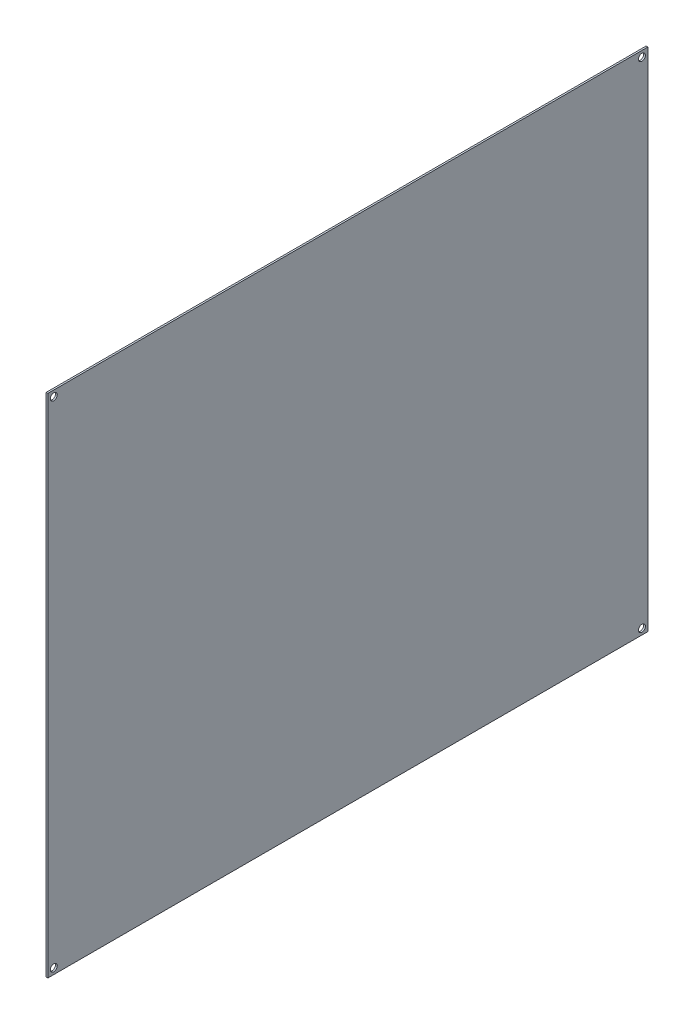
SolidWorks part; units mm, degrees
ref_plane "Front Plane" through (0, 0, 0) normal (0, 0, 1) x (1, 0, 0)
ref_plane "Top Plane" through (0, 0, 0) normal (0, 1, 0) x (1, 0, 0)
ref_plane "Right Plane" through (0, 0, 0) normal (1, 0, 0) x (0, 0, -1)
sketch "Sketch1" plane through (-873.1278, 0, 0) normal (-1, 0, 0) x (0, 0, 1)
  line L0 (-594.3, 508.1004) -> (-594.3, 38.0999) construction
  line L2 (-594.3, 508.1004) -> (-38.1, 508.1004) construction
  line L3 (-38.1, 38.0999) -> (-38.1, 508.1004) construction
  line L4 (-594.3, 508.1004) -> (-38.1, 508.1004) construction
  line L5 (-592.3, 506.1004) -> (-592.3, 40.0999)
  line L6 (-594.3, 38.0999) -> (-38.1, 38.0999) construction
  line L8 (-594.3, 38.0999) -> (-38.1, 38.0999) construction
  line L9 (-592.3, 40.0999) -> (-40.1, 40.0999)
  line L10 (-40.1, 40.0999) -> (-40.1, 506.1004)
  line L11 (-592.3, 506.1004) -> (-40.1, 506.1004)
  circle A0 centre (-586.859, 500.659) radius 3.175 construction
  circle A1 centre (-45.541, 500.659) radius 3.175 construction
  circle A2 centre (-45.541, 45.541) radius 3.175 construction
  circle A3 centre (-586.859, 45.541) radius 3.175 construction
  circle A4 centre (-586.859, 500.659) radius 3.175
  circle A5 centre (-45.541, 500.659) radius 3.175
  circle A6 centre (-45.541, 45.541) radius 3.175
  circle A7 centre (-586.859, 45.541) radius 3.175
extrude "Boss-Extrude1" add sketch "Sketch1" along normal blind 1.6002
